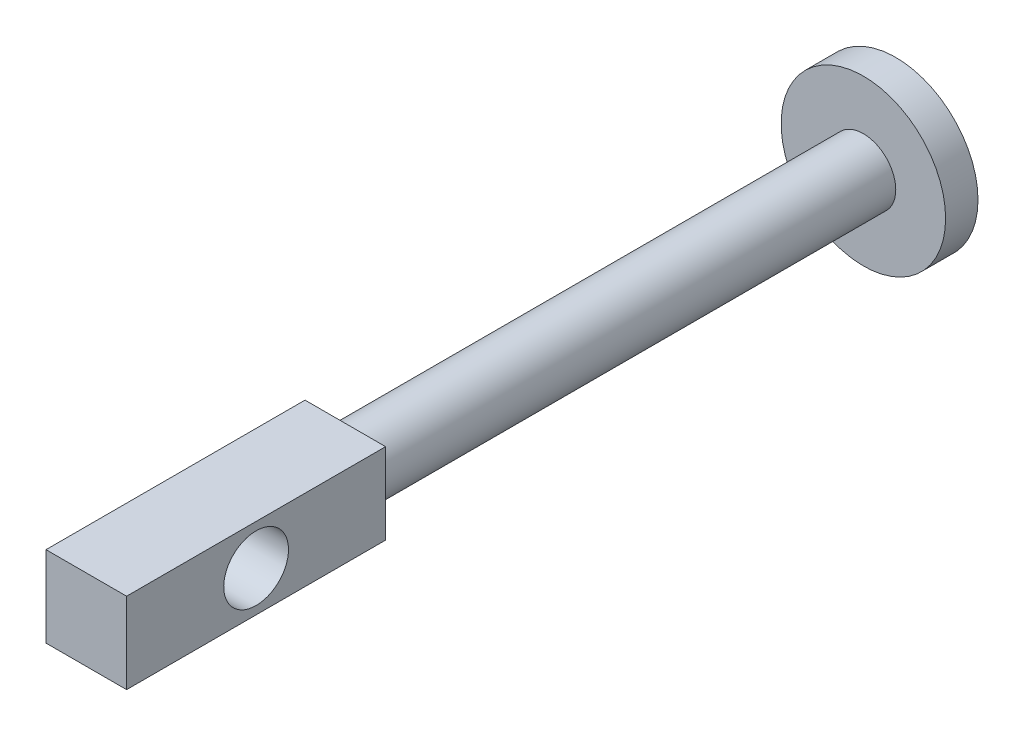
SolidWorks part; units mm, degrees
ref_plane "Front Plane" through (0, 0, 0) normal (0, 0, 1) x (1, 0, 0)
ref_plane "Top Plane" through (0, 0, 0) normal (0, 1, 0) x (1, 0, 0)
ref_plane "Right Plane" through (0, 0, 0) normal (1, 0, 0) x (0, 0, -1)
sketch "Sketch1" plane through (0, 0, 0) normal (0, 0, 1) x (1, 0, 0)
  circle A0 centre (0, 0) radius 12.7
  dimension "D1" = 25.4
extrude "Boss-Extrude1" add sketch "Sketch1" along normal blind 5
sketch "Sketch2" plane through (0, 0, 5) normal (0, 0, 1) x (1, 0, 0)
  circle A0 centre (0, 0) radius 5
  dimension "D1" = 10
extrude "Boss-Extrude3" add sketch "Sketch2" along normal blind 80 contours A0
sketch "Sketch3" plane through (0, 0, 85) normal (0, 0, 1) x (1, 0, 0)
  line L1 (6.223, 6.25) -> (-6.223, 6.25)
  line L2 (6.223, 6.25) -> (6.223, -6.25)
  line L3 (6.223, -6.25) -> (-6.223, -6.25)
  line L4 (-6.223, 6.25) -> (-6.223, -6.25)
  line L5 (6.223, 6.25) -> (-6.223, -6.25) construction
  line L6 (6.223, -6.25) -> (-6.223, 6.25) construction
  point P0 (0, 0)
  dimension "D1" = 12.5
  dimension "D2" = 12.446
extrude "Boss-Extrude4" add sketch "Sketch3" along normal blind 40
sketch "Sketch4" plane through (-6.223, 0, 0) normal (-1, 0, 0) x (0, 0, 1)
  line L0 (85, 0) -> (128.0235, 0) construction
  line L1 (85, 6.25) -> (85, -6.25) construction
  circle A0 centre (105, 0) radius 5
  dimension "D1" = 10
  dimension "D2" = 20
extrude "Cut-Extrude1" cut sketch "Sketch4" against normal through all
